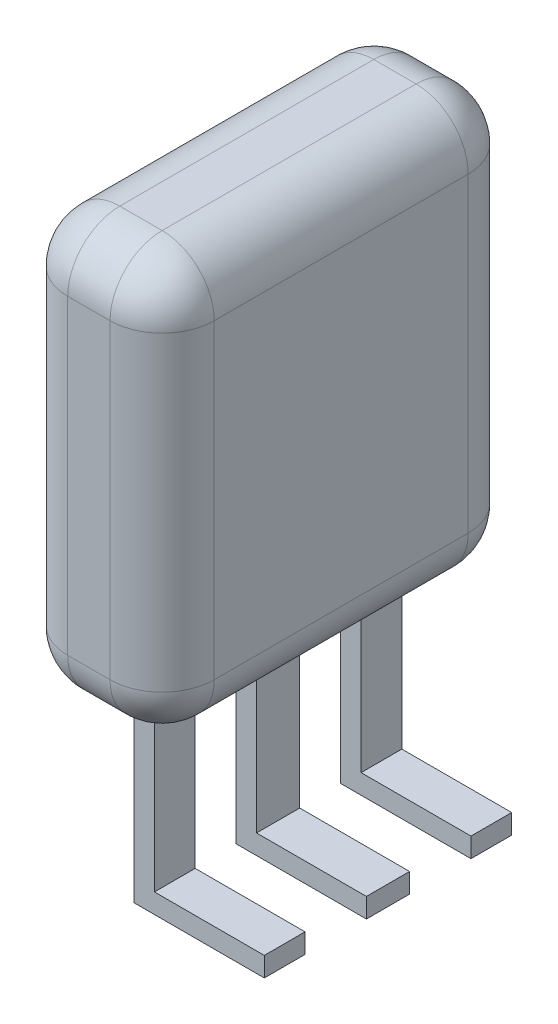
SolidWorks part; units mm, degrees
ref_plane "Front Plane" through (0, 0, 0) normal (0, 0, 1) x (1, 0, 0)
ref_plane "Top Plane" through (0, 0, 0) normal (0, 1, 0) x (1, 0, 0)
ref_plane "Right Plane" through (0, 0, 0) normal (1, 0, 0) x (0, 0, -1)
sketch "Sketch1" plane through (0, 0, 0) normal (1, 0, 0) x (0, 0, -1)
  line L1 (-1.56, 2.55) -> (1.56, 2.55)
  line L2 (-2.2, 1.91) -> (-2.2, -1.91)
  line L3 (-1.56, -2.55) -> (1.56, -2.55)
  line L4 (2.2, 1.91) -> (2.2, -1.91)
  line L5 (-2.2, 2.55) -> (2.2, -2.55) construction
  line L6 (-2.2, -2.55) -> (2.2, 2.55) construction
  arc A0 (-2.2, -1.91) -> (-1.56, -2.55) centre (-1.56, -1.91) ccw
  arc A1 (1.56, -2.55) -> (2.2, -1.91) centre (1.56, -1.91) ccw
  arc A2 (1.56, 2.55) -> (2.2, 1.91) centre (1.56, 1.91) cw
  arc A3 (-1.56, 2.55) -> (-2.2, 1.91) centre (-1.56, 1.91) ccw
  point P0 (0, 0)
  dimension "D3" = 0.64
  dimension "D1" = 4.4
  dimension "D2" = 5.1
extrude "Boss-Extrude1" add sketch "Sketch1" along normal blind 1.8
fillet "Fillet1" radius 0.64 16 edges at (1.8, 2.3625, -2.0125) (1.8, 0, -2.2) (1.8, -2.3625, -2.0125) (1.8, -2.55, 0) (1.8, -2.3625, 2.0125) (1.8, 0, 2.2) (1.8, 2.3625, 2.0125) (0, 2.3625, -2.0125) (0, 0, -2.2) (0, -2.3625, -2.0125) (0, -2.55, 0) (0, -2.3625, 2.0125) (0, 0, 2.2) (0, 2.3625, 2.0125) (1.8, 2.55, 0) (0, 2.55, 0)
ref_plane "Plane1" through (0.9, 0, 0) normal (1, 0, 0) x (0, 0, -1)
sketch "Sketch2" plane through (0.9, 0, 0) normal (1, 0, 0) x (0, 0, -1)
  line L0 (0, 0) -> (0, -3.8385) construction
  line L1 (0, -3.8385) -> (0, -4.5751) construction
  line L7 (0.2346, -1.6928) -> (0.2346, -1.09)
  line L8 (-1.5199, -1.5016) -> (-1.5199, -4.5751)
  line L9 (-1.0191, -2.2634) -> (-1.0191, -4.5751)
  line L13 (1.0191, -2.2634) -> (1.0191, -4.5751)
  line L14 (1.5199, -1.5016) -> (1.5199, -4.5751)
  line L15 (1.5199, -1.5016) -> (1.5199, 1.91)
  line L16 (0.2653, -4.5751) -> (0.2653, -2.1172)
  line L17 (0, -2.55) -> (0, -4.5751) construction
  line L18 (1.56, -2.55) -> (-1.56, -2.55) construction
  line L19 (0.2653, -2.1172) -> (0.7172, -2.1172)
  line L20 (0.7172, -2.1172) -> (0.7172, -1.6928)
  line L21 (1.56, 1.91) -> (-1.56, 1.91) construction
  line L22 (0.7172, -1.6928) -> (0.2346, -1.6928)
  line L23 (0.2346, -1.09) -> (0.6829, -1.09)
  line L24 (0.6829, -1.09) -> (0.6829, -0.4789)
  line L26 (-0.2653, -2.1172) -> (-0.7172, -2.1172)
  line L27 (-0.7172, -2.1172) -> (-0.7172, -1.6928)
  line L28 (-0.7172, -1.6928) -> (-0.2346, -1.6928)
  line L29 (-0.2346, -1.6928) -> (-0.2346, -1.09)
  line L30 (0.6829, -0.4789) -> (-0.6829, -0.4789)
  line L31 (-0.2346, -1.09) -> (-0.6829, -1.09)
  line L32 (-0.6829, -1.09) -> (-0.6829, -0.4789)
  line L33 (1.0191, -2.2634) -> (1.0191, 1.11)
  line L34 (1.0191, 1.11) -> (0.357, 1.11)
  line L35 (0.357, 1.11) -> (0.357, 1.7618)
  line L36 (0.357, 1.7618) -> (-0.8142, 1.7618)
  line L37 (-0.8142, 1.7618) -> (-0.8142, 2.2812)
  line L38 (-0.8142, 2.2812) -> (1.5199, 2.2812)
  line L39 (1.5199, -4.5751) -> (1.0191, -4.5751)
  line L40 (1.5199, 2.2812) -> (1.5199, 1.91)
  line L41 (-1.5199, -1.5016) -> (-1.5199, 2.2812)
  line L42 (-1.5199, 2.2812) -> (-1.0191, 2.2812)
  line L43 (-1.0191, 2.2812) -> (-1.0191, 1.2729)
  line L44 (-1.0191, 1.2729) -> (-0.1217, 1.2729)
  line L45 (-0.1217, 1.2729) -> (-0.1217, 0.7026)
  line L46 (-0.1217, 0.7026) -> (0.7172, 0.7026)
  line L47 (0.7172, 0.7026) -> (0.7172, -0.0919)
  line L48 (0.7172, -0.0919) -> (-1.0191, -0.0919)
  line L49 (-1.0191, -0.0919) -> (-1.0191, -2.2634)
  line L50 (-1.56, -1.91) -> (1.56, -1.91) construction
  line L51 (0.2653, -4.5751) -> (-0.2653, -4.5751)
  line L52 (-1.0191, -4.5751) -> (-1.5199, -4.5751)
  line L54 (-0.2653, -4.5751) -> (-0.2653, -2.1172)
  circle A0 centre (-1.2695, -1.91) radius 0.1581
  circle A1 centre (1.2635, -1.91) radius 0.1597
  point P40 (0, -0.5712)
  point P45 (0, -0.4789)
extrude "Boss-Extrude2" add sketch "Sketch2" along normal blind 0.125 and the other way blind 0.125 separate body
sketch "Sketch4" plane through (0.775, 0, 0) normal (1, 0, 0) x (0, 0, -1)
  line L1 (-1.5199, -4.5751) -> (-1.0191, -4.5751)
  line L2 (-1.5199, -4.5751) -> (-1.5199, -4.8159)
  line L3 (-1.5199, -4.8159) -> (-1.0191, -4.8159)
  line L4 (-1.0191, -4.5751) -> (-1.0191, -4.8159)
  line L5 (-0.2653, -4.5751) -> (0.2653, -4.5751)
  line L6 (-0.2653, -4.5751) -> (-0.2653, -4.8159)
  line L7 (-0.2653, -4.8159) -> (0.2653, -4.8159)
  line L8 (0.2653, -4.5751) -> (0.2653, -4.8159)
  line L9 (1.0191, -4.5751) -> (1.5199, -4.5751)
  line L10 (1.0191, -4.5751) -> (1.0191, -4.8159)
  line L11 (1.0191, -4.8159) -> (1.5199, -4.8159)
  line L12 (1.5199, -4.5751) -> (1.5199, -4.8159)
extrude "Boss-Extrude3" add sketch "Sketch4" along normal blind 1.6
